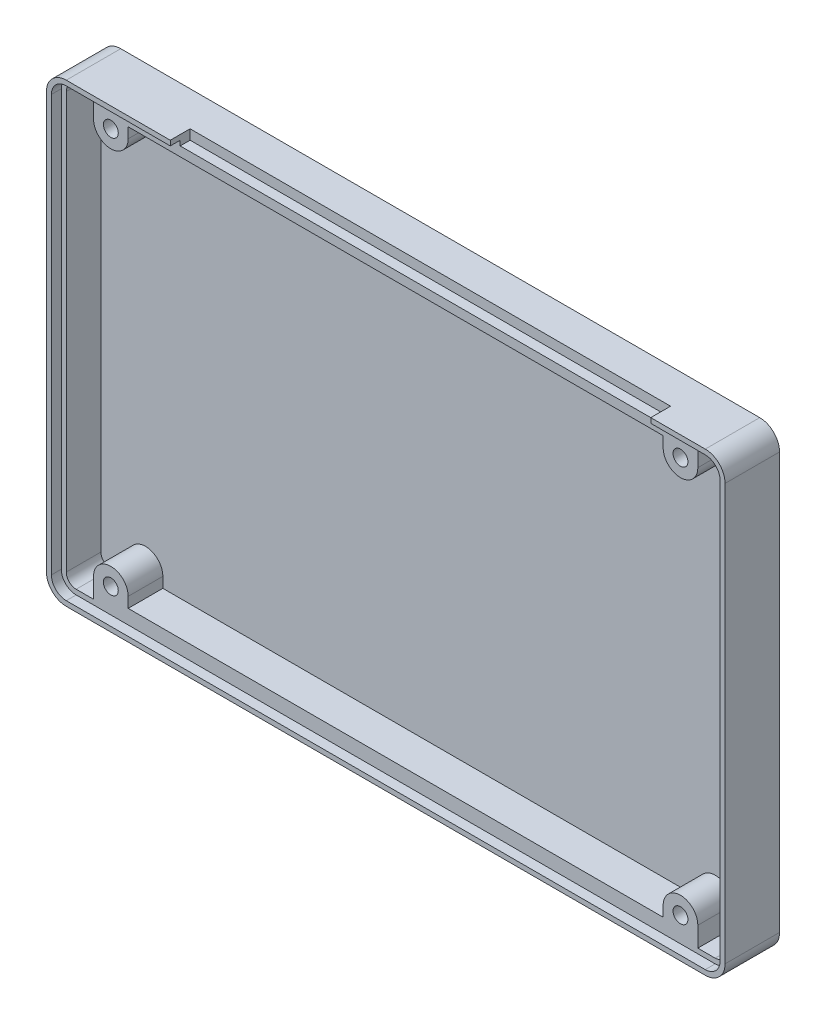
SolidWorks part; units mm, degrees
ref_plane "Front Plane" through (0, 0, 0) normal (0, 0, 1) x (1, 0, 0)
ref_plane "Top Plane" through (0, 0, 0) normal (0, 1, 0) x (1, 0, 0)
ref_plane "Right Plane" through (0, 0, 0) normal (1, 0, 0) x (0, 0, -1)
sketch "Sketch1" plane through (0, 0, 0) normal (0, 0, 1) x (1, 0, 0)
  line L1 (0, 0) -> (137, 0)
  line L2 (0, 0) -> (0, 92)
  line L3 (0, 92) -> (137, 92)
  line L4 (137, 0) -> (137, 92)
  dimension "D1" = 137
  dimension "D2" = 92
extrude "Boss-Extrude1" add sketch "Sketch1" along normal blind 2
sketch "Sketch2" plane through (0, 0, 2) normal (0, 0, 1) x (1, 0, 0)
  line L1 (0, 92) -> (137, 92)
  line L2 (0, 92) -> (0, 0)
  line L3 (0, 0) -> (137, 0)
  line L4 (137, 92) -> (137, 0)
  line L5 (2, 2) -> (135, 2)
  line L6 (2, 2) -> (2, 90)
  line L7 (2, 90) -> (135, 90)
  line L8 (135, 2) -> (135, 90)
  dimension "D1" = 2
  dimension "D2" = 2
  dimension "D3" = 2
  dimension "D4" = 2
extrude "Boss-Extrude2" add sketch "Sketch2" along normal blind 7
sketch "Sketch3" plane through (0, 0, 9) normal (0, 0, 1) x (1, 0, 0)
  line L1 (0, 0) -> (137, 0)
  line L2 (0, 0) -> (0, 92)
  line L3 (0, 92) -> (137, 92)
  line L4 (137, 0) -> (137, 92)
  line L5 (1, 1) -> (136, 1)
  line L6 (1, 1) -> (1, 91)
  line L7 (1, 91) -> (136, 91)
  line L8 (136, 1) -> (136, 91)
  dimension "D1" = 1
  dimension "D2" = 1
  dimension "D3" = 1
  dimension "D4" = 1
extrude "Boss-Extrude3" add sketch "Sketch3" along normal blind 2
sketch "Sketch4" plane through (0, 0, 2) normal (0, 0, 1) x (1, 0, 0)
  line L0 (0, 0) -> (137, 0) construction
  line L1 (0, 92) -> (0, 0) construction
  line L2 (2, 2) -> (135, 2) construction
  line L4 (7.5, 6) -> (7.5, 2)
  line L5 (7.5, 2) -> (14.5, 2)
  line L6 (14.5, 6) -> (14.5, 2)
  line L7 (137, 0) -> (137, 92) construction
  line L8 (137, 92) -> (0, 92) construction
  line L9 (2, 2) -> (135, 2) construction
  line L11 (122.5, 6) -> (122.5, 2)
  line L12 (122.5, 2) -> (129.5, 2)
  line L13 (129.5, 6) -> (129.5, 2)
  line L14 (135, 90) -> (2, 90) construction
  line L16 (129.5, 86) -> (129.5, 90)
  line L17 (129.5, 90) -> (122.5, 90)
  line L18 (122.5, 86) -> (122.5, 90)
  line L19 (135, 90) -> (2, 90) construction
  line L21 (14.5, 86) -> (14.5, 90)
  line L22 (14.5, 90) -> (7.5, 90)
  line L23 (7.5, 86) -> (7.5, 90)
  arc A0 (14.5, 6) -> (7.5, 6) centre (11, 6) ccw
  circle A1 centre (11, 6) radius 1.5
  arc A2 (7.5, 86) -> (14.5, 86) centre (11, 86) ccw
  circle A3 centre (11, 86) radius 1.5
  arc A4 (122.5, 86) -> (129.5, 86) centre (126, 86) ccw
  circle A5 centre (126, 86) radius 1.5
  arc A6 (129.5, 6) -> (122.5, 6) centre (126, 6) ccw
  circle A7 centre (126, 6) radius 1.5
  dimension "D1" = 3
  dimension "D2" = 7
  dimension "D3" = 3
  dimension "D4" = 7
  dimension "D5" = 3
  dimension "D6" = 7
  dimension "D7" = 3
  dimension "D8" = 7
  dimension "D11" = 6
  dimension "D9" = 6
  dimension "D10" = 11
  dimension "D12" = 11
  dimension "D13" = 11
  dimension "D14" = 6
  dimension "D15" = 11
  dimension "D16" = 6
extrude "Boss-Extrude4" add sketch "Sketch4" along normal blind 7
sketch "Sketch8" plane through (0, 0, 2) normal (0, 0, 1) x (1, 0, 0)
  line L0 (122.5, 6) -> (122.5, 2) construction
  line L1 (14.5, 2) -> (122.5, 2)
  line L2 (14.5, 2) -> (14.5, 3.9)
  line L3 (14.5, 3.9) -> (122.5, 3.9)
  line L4 (122.5, 2) -> (122.5, 3.9)
  dimension "D1" = 1.9
extrude "Boss-Extrude6" add sketch "Sketch8" along normal blind 7
fillet "Fillet1" radius 2 4 edges at (2, 2, 5.5) (135, 2, 5.5) (135, 90, 5.5) (2, 90, 5.5)
fillet "Fillet2" radius 3 4 edges at (1, 1, 10) (136, 1, 10) (136, 91, 10) (1, 91, 10)
fillet "Fillet3" radius 4 4 edges at (137, 92, 5.5) (0, 92, 5.5) (0, 0, 5.5) (137, 0, 5.5)
sketch "Sketch11" plane through (0, 0, 2) normal (0, 0, 1) x (1, 0, 0)
  line L0 (122.5, 90) -> (122.5, 86) construction
  line L1 (14.5, 90) -> (122.5, 90)
  line L2 (14.5, 90) -> (14.5, 88.1)
  line L3 (14.5, 88.1) -> (122.5, 88.1)
  line L4 (122.5, 90) -> (122.5, 88.1)
  dimension "D1" = 1.9
extrude "Boss-Extrude7" add sketch "Sketch11" along normal blind 7
sketch "Sketch12" plane through (0, 92, 0) normal (0, 1, 0) x (1, 0, 0)
  line L0 (133, -11) -> (4, -11) construction
  line L1 (25, -11) -> (122, -11)
  line L2 (25, -11) -> (25, -7)
  line L3 (25, -7) -> (122, -7)
  line L4 (122, -11) -> (122, -7)
  line L5 (0, -11) -> (0, 0) construction
  dimension "D1" = 4
  dimension "D2" = 97
  dimension "D3" = 25
extrude "Cut-Extrude3" cut sketch "Sketch12" against normal blind 2
sketch "Sketch13" plane through (0, 0, 9) normal (0, 0, 1) x (1, 0, 0)
  circle A0 centre (11, 86) radius 1.5
  circle A1 centre (11, 6) radius 1.5
  circle A2 centre (126, 6) radius 1.5
  circle A3 centre (126, 86) radius 1.5
extrude "Cut-Extrude4" cut sketch "Sketch13" against normal blind 10
